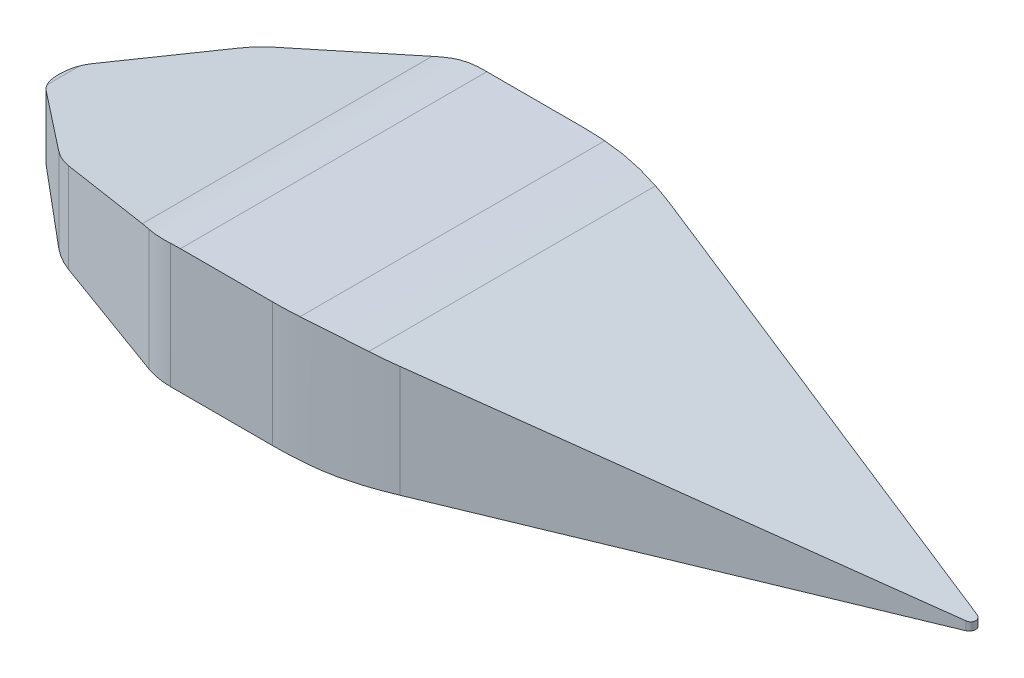
SolidWorks part; units mm, degrees
ref_plane "Front Plane" through (0, 0, 0) normal (0, 0, 1) x (1, 0, 0)
ref_plane "Top Plane" through (0, 0, 0) normal (0, 1, 0) x (1, 0, 0)
ref_plane "Right Plane" through (0, 0, 0) normal (1, 0, 0) x (0, 0, -1)
sketch "Sketch1" plane through (0, 0, 0) normal (0, 1, 0) x (1, 0, 0)
  line L0 (146.0698, 122.5671) -> (556.1483, 466.6637)
  line L1 (676.4552, 536.1229) -> (1335.1737, 775.877)
  line L2 (1471.9818, 800) -> (2005.9909, 800)
  line L3 (2584.2902, 714.5678) -> (4854.922, 28.7185)
  line L4 (4854.922, -28.7185) -> (2584.2902, -714.5678)
  line L5 (2005.9909, -800) -> (1471.9818, -800)
  line L6 (1335.1737, -775.877) -> (676.4552, -536.1229)
  line L7 (556.1483, -466.6637) -> (146.0698, -122.5671)
  arc A0 (146.0698, 122.5671) -> (146.0698, -122.5671) centre (248.9159, 0) ccw
  arc A1 (676.4552, -536.1229) -> (556.1483, -466.6637) centre (813.2633, -160.2459) cw
  arc A2 (1471.9818, -800) -> (1335.1737, -775.877) centre (1471.9818, -400) cw
  arc A3 (1335.1737, 775.877) -> (1471.9818, 800) centre (1471.9818, 400) cw
  arc A4 (556.1483, 466.6637) -> (676.4552, 536.1229) centre (813.2633, 160.2459) cw
  arc A5 (2584.2902, -714.5678) -> (2005.9909, -800) centre (2005.9909, 1200) cw
  arc A6 (2005.9909, 800) -> (2584.2902, 714.5678) centre (2005.9909, -1200) cw
  arc A7 (4854.922, 28.7185) -> (4854.922, -28.7185) centre (4846.2475, 0) cw
  point P11 (0, 0)
  point P14 (610.178, -512)
  point P17 (1401.451, -800)
  point P20 (1401.451, 800)
  point P23 (610.178, 512)
  point P26 (2301.451, -800)
  point P29 (2301.451, 800)
  point P32 (4950, 0)
  dimension "r0" = 160
  dimension "r1" = 400
  dimension "r3" = 2000
  dimension "r4" = 30
  dimension "x1" = 610.178
  dimension "x2" = 1401.451
  dimension "x3" = 2301.451
  dimension "x4" = 4950
  dimension "x5" = 2301.451
  dimension "x6" = 1401.451
  dimension "x7" = 610.178
  dimension "y1" = 512
  dimension "y2" = 800
  dimension "y5" = 800
  dimension "y7" = 512
extrude "TopView_Extrude" add sketch "Sketch1" along normal blind 800
sketch "Sketch2" plane through (0, 0, 0) normal (0, 0, 1) x (1, 0, 0)
  line L0 (0, 300) -> (0, 332.8541)
  line L1 (113.6551, 478.3844) -> (1282.1337, 770.2016)
  line L2 (1524.433, 800) -> (2144.4827, 800)
  line L3 (2456.4974, 775.5118) -> (4950, 381.685)
  line L4 (4950, 381.685) -> (4950, 359.158)
  line L5 (4950, 359.158) -> (2419.356, 159.311)
  line L6 (2183.1789, 150) -> (150, 150)
  arc A0 (0, 332.8541) -> (113.6551, 478.3844) centre (150, 332.8541) cw
  arc A1 (0, 300) -> (150, 150) centre (150, 300) ccw
  arc A2 (1282.1337, 770.2016) -> (1524.433, 800) centre (1524.433, -200) cw
  arc A3 (2144.4827, 800) -> (2456.4974, 775.5118) centre (2144.4827, -1200) cw
  arc A4 (2419.356, 159.311) -> (2183.1789, 150) centre (2183.1789, 3150) cw
  point P10 (0, 450)
  point P13 (0, 150)
  point P16 (1401.451, 800)
  point P19 (2301.451, 800)
  point P22 (2301.451, 150)
  dimension "r0" = 150
  dimension "r2" = 1000
  dimension "r3" = 2000
  dimension "r6" = 3000
  dimension "x2" = 1401.451
  dimension "x3" = 2301.451
  dimension "x4" = 4950
  dimension "x6" = 2301.451
  dimension "y0" = 150
  dimension "y1" = 450
  dimension "y2" = 800
  dimension "y4" = 381.685
  dimension "y5" = 359.158
extrude "SideProfile_Cut" cut sketch "Sketch2" against normal through all and the other way through all flip side to cut
